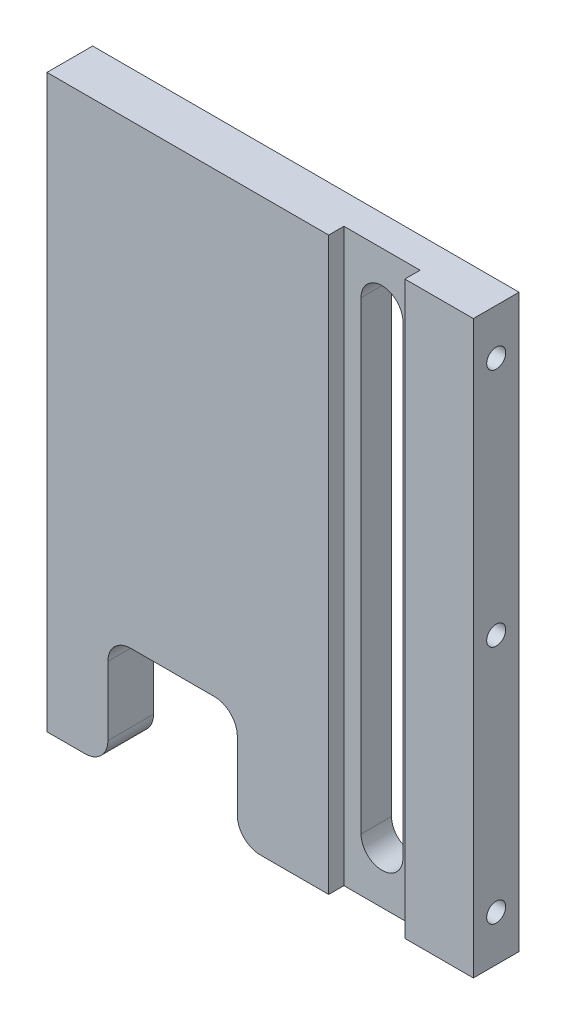
SolidWorks part; units mm, degrees
material "Сплав 2024"
ref_plane "Спереди" through (0, 0, 0) normal (0, 0, 1) x (1, 0, 0)
ref_plane "Сверху" through (0, 0, 0) normal (0, 1, 0) x (1, 0, 0)
ref_plane "Справа" through (0, 0, 0) normal (1, 0, 0) x (0, 0, -1)
sketch "Эскиз1" plane through (0, 0, 0) normal (0, 0, 1) x (1, 0, 0)
  line L1 (-28, 37.5) -> (28, 37.5)
  line L2 (-28, 37.5) -> (-28, -37.5)
  line L3 (-28, -37.5) -> (28, -37.5)
  line L4 (28, 37.5) -> (28, -37.5)
  line L5 (-28, 37.5) -> (28, -37.5) construction
  line L6 (-28, -37.5) -> (28, 37.5) construction
  point P0 (0, 0)
  dimension "D1" = 75
  dimension "D2" = 56
extrude "Бобышка-Вытянуть1" add sketch "Эскиз1" along normal blind 6
sketch "Эскиз2" plane through (0, 0, 6) normal (0, 0, 1) x (1, 0, 0)
  line L0 (14, 37.5) -> (14, -37.5) construction
  line L1 (28, 37.5) -> (-28, 37.5) construction
  line L2 (-28, -37.5) -> (28, -37.5) construction
  line L3 (28, -37.5) -> (28, 37.5) construction
  line L4 (14, 30.5) -> (14, -30.5) construction
  line L5 (16.75, 30.5) -> (16.75, -30.5)
  line L6 (11.25, 30.5) -> (11.25, -30.5)
  arc A0 (16.75, 30.5) -> (11.25, 30.5) centre (14, 30.5) ccw
  arc A1 (11.25, -30.5) -> (16.75, -30.5) centre (14, -30.5) ccw
  point P10 (14, 0)
  dimension "D2" = 2.75
  dimension "D1" = 14
  dimension "D3" = 7
  dimension "D4" = 7
  dimension "D5" = 61
extrude "Вырез-Вытянуть1" cut sketch "Эскиз2" against normal through all
sketch "Эскиз3" plane through (-28, 0, 0) normal (-1, 0, 0) x (0, 0, 1)
  line L0 (3, 37.5) -> (3, -37.5) construction
  line L1 (6, 37.5) -> (0, 37.5) construction
  line L2 (6, -37.5) -> (0, -37.5) construction
  line L3 (0, 0) -> (6, 0) construction
  line L4 (6, 37.5) -> (6, -37.5) construction
  line L5 (0, 31.5) -> (6, 31.5) construction
  line L6 (0, 37.5) -> (0, -37.5) construction
  line L7 (0, -31.5) -> (6, -31.5) construction
  dimension "D1" = 6
  dimension "D2" = 6
hole_wizard "Отверстие обработанное метчиком M3x0.51" positions "Эскиз5" profile "Эскиз4" tap size "M3x0.5" standard "Ansi Metric"
sketch "Эскиз5" plane through (-28, 0, 0) normal (-1, 0, 0) x (0, 0, 1)
  line L0 (0, 31.5) -> (6, 31.5) construction
  line L1 (3, 37.5) -> (3, -37.5) construction
  line L2 (0, -31.5) -> (6, -31.5) construction
  point P0 (3, 31.5)
  point P4 (3, 0)
  point P8 (3, -31.5)
sketch "Эскиз4" plane through (-28, 31.5, 3) normal (0, 1, 0) x (0, 0, 1)
  line L0 (0, 0) -> (0, 6.7511)
  line L1 (0, 6.7511) -> (1.25, 6)
  line L2 (1.25, 6) -> (1.25, 0)
  line L5 (1.25, 0) -> (0, 0)
  line L10 (0, 6.7511) -> (-1.25, 6) construction
  line L11 (0, -6.35) -> (0, 107.95) construction
  dimension "Диаметр сверла" = 2.5
  dimension "Глубина сверла" = 6
  dimension "Угол заточки сверла" = 118
cosmetic thread "Отверстие резьбы1" parameters "D1"=6, "D2"=3
cosmetic thread "Отверстие резьбы2" parameters "D1"=6, "D2"=3
cosmetic thread "Отверстие резьбы3" parameters "D1"=6, "D2"=3
ref_plane "Плоскость1" through (0, 0, 0) normal (-1, 0, 0) x (0, 0, 1)
mirror "Зеркальное отражение1" about plane through (0, 0, 0) normal (-1, 0, 0) of "Отверстие обработанное метчиком M3x0.51"
sketch "Эскиз6" plane through (0, 0, 6) normal (0, 0, 1) x (1, 0, 0)
  line L0 (-28, -37.5) -> (28, -37.5) construction
  line L1 (19, 37.5) -> (9, 37.5)
  line L2 (19, 37.5) -> (19, -37.5)
  line L3 (19, -37.5) -> (9, -37.5)
  line L4 (9, 37.5) -> (9, -37.5)
  line L5 (19, 37.5) -> (9, -37.5) construction
  line L6 (19, -37.5) -> (9, 37.5) construction
  point P0 (14, 0)
  dimension "D1" = 10
extrude "Вырез-Вытянуть2" cut sketch "Эскиз6" against normal blind 2
sketch "Эскиз7" plane through (0, 0, 6) normal (0, 0, 1) x (1, 0, 0)
  line L0 (-11.5, 37.5) -> (-11.5, -37.5) construction
  line L1 (9, 37.5) -> (-28, 37.5) construction
  line L2 (-28, -37.5) -> (9, -37.5) construction
  line L3 (-28, 37.5) -> (-28, -37.5) construction
  line L5 (-20, -22.5) -> (-3, -22.5)
  line L6 (-20, -22.5) -> (-20, -37.5)
  line L7 (-20, -37.5) -> (-3, -37.5)
  line L8 (-3, -22.5) -> (-3, -37.5)
  line L9 (-20, -22.5) -> (-3, -37.5) construction
  line L10 (-20, -37.5) -> (-3, -22.5) construction
  point P8 (-11.5, -30)
  dimension "D1" = 16.5
  dimension "D2" = 17
  dimension "D3" = 15
extrude "Вырез-Вытянуть3" cut sketch "Эскиз7" against normal through all
fillet "Скругление1" radius 3 4 edges at (-20, -37.5, 3) (-3, -37.5, 3) (-3, -22.5, 3) (-20, -22.5, 3)
